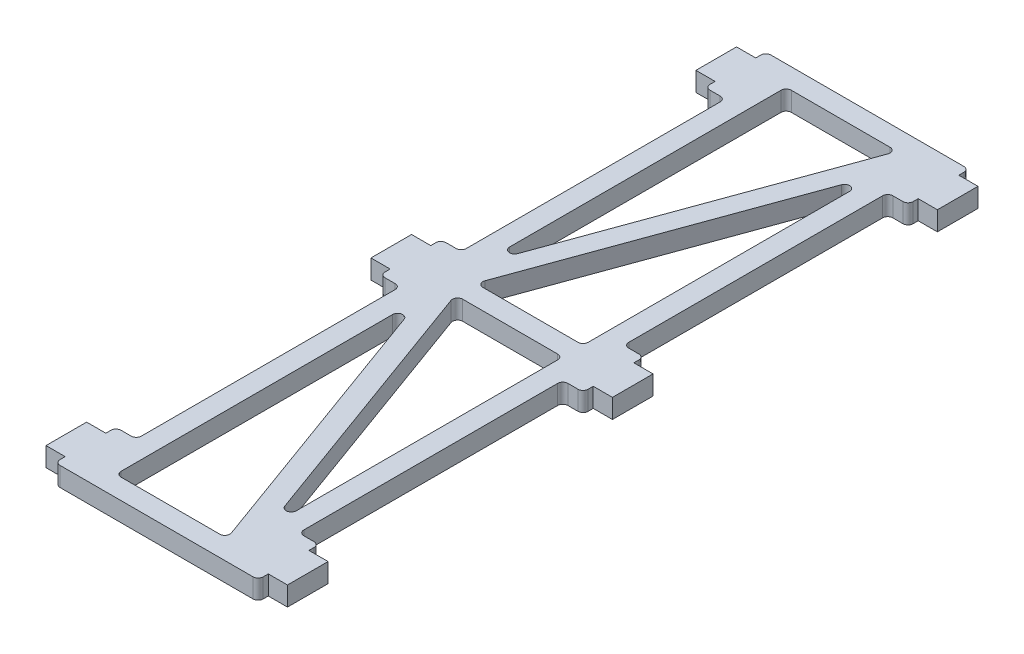
SolidWorks part; units mm, degrees
ref_plane "Front Plane" through (0, 0, 0) normal (0, 0, 1) x (1, 0, 0)
ref_plane "Top Plane" through (0, 0, 0) normal (0, 1, 0) x (1, 0, 0)
ref_plane "Right Plane" through (0, 0, 0) normal (1, 0, 0) x (0, 0, -1)
sketch "Sketch1" plane through (0, 34.29, 0) normal (0, 1, 0) x (1, 0, 0)
  line L0 (16.0528, 190.5) -> (19.05, 190.5) construction
  line L1 (0, -190.5) -> (0, 187.198) construction
  line L2 (38.1028, 187.198) -> (35.1028, 187.198) construction
  line L3 (35.1028, -190.5) -> (38.1, -190.5) construction
  line L5 (-12.7, 65.0875) -> (12.7, 65.0875)
  line L6 (-12.7, 65.0875) -> (-12.7, 176.2125)
  line L7 (-12.7, 176.2125) -> (12.7, 176.2125)
  line L8 (12.7, 65.0875) -> (12.7, 176.2125)
  line L9 (-12.7, 65.0875) -> (12.7, 176.2125) construction
  line L10 (-12.7, 176.2125) -> (12.7, 65.0875) construction
  point P0 (0, 120.65)
  dimension "D1" = 111.125
  dimension "D2" = 25.4
  dimension "D3" = 14.2875
extrude "Boss-Extrude1" add sketch "Sketch1" along normal mid plane 3 contours L7 L8 L5 L6
sketch "Sketch2" plane through (0, 35.79, 0) normal (0, 1, 0) x (1, 0, 0)
  line L0 (0, 176.2125) -> (0, 65.0186) construction
  line L1 (-12.7, 176.2125) -> (12.7, 176.2125) construction
  line L2 (12.7, 120.65) -> (-12.7, 120.65) construction
  line L3 (12.7, 65.0875) -> (12.7, 176.2125) construction
  line L4 (-12.7, 65.0875) -> (-12.7, 176.2125) construction
  line L5 (-15.875, 176.2125) -> (-12.7, 166.6875) construction
  line L6 (15.875, 166.6875) -> (12.7, 166.6875)
  line L7 (15.875, 166.6875) -> (15.875, 176.2125)
  line L8 (15.875, 176.2125) -> (12.7, 176.2125)
  line L9 (12.7, 166.6875) -> (12.7, 176.2125)
  line L10 (15.875, 166.6875) -> (12.7, 176.2125) construction
  line L11 (15.875, 176.2125) -> (12.7, 166.6875) construction
  line L12 (-15.875, 166.6875) -> (-12.7, 176.2125) construction
  line L13 (-12.7, 166.6875) -> (-12.7, 176.2125)
  line L14 (-15.875, 176.2125) -> (-12.7, 176.2125)
  line L15 (-15.875, 166.6875) -> (-15.875, 176.2125)
  line L16 (-15.875, 166.6875) -> (-12.7, 166.6875)
  line L17 (15.875, 115.8875) -> (12.7, 115.8875)
  line L18 (15.875, 115.8875) -> (15.875, 125.4125)
  line L19 (15.875, 125.4125) -> (12.7, 125.4125)
  line L20 (12.7, 115.8875) -> (12.7, 125.4125)
  line L21 (15.875, 115.8875) -> (12.7, 125.4125) construction
  line L22 (15.875, 125.4125) -> (12.7, 115.8875) construction
  line L23 (-12.7, 115.8875) -> (-12.7, 125.4125)
  line L24 (-15.875, 125.4125) -> (-12.7, 125.4125)
  line L25 (-15.875, 115.8875) -> (-15.875, 125.4125)
  line L26 (-15.875, 115.8875) -> (-12.7, 115.8875)
  line L27 (-15.875, 125.4125) -> (-12.7, 115.8875) construction
  line L28 (-15.875, 115.8875) -> (-12.7, 125.4125) construction
  line L29 (15.875, 65.0875) -> (12.7, 65.0875)
  line L30 (15.875, 65.0875) -> (15.875, 74.6125)
  line L31 (15.875, 74.6125) -> (12.7, 74.6125)
  line L32 (12.7, 65.0875) -> (12.7, 74.6125)
  line L33 (15.875, 65.0875) -> (12.7, 74.6125) construction
  line L34 (15.875, 74.6125) -> (12.7, 65.0875) construction
  line L35 (-12.7, 65.0875) -> (-12.7, 74.6125)
  line L36 (-15.875, 74.6125) -> (-12.7, 74.6125)
  line L37 (-15.875, 65.0875) -> (-15.875, 74.6125)
  line L38 (-15.875, 65.0875) -> (-12.7, 65.0875)
  line L39 (-15.875, 74.6125) -> (-12.7, 65.0875) construction
  line L40 (-15.875, 65.0875) -> (-12.7, 74.6125) construction
  point P11 (14.2875, 171.45)
  point P21 (-14.2875, 171.45)
  point P24 (14.2875, 120.65)
  point P33 (-14.2875, 120.65)
  point P34 (14.2875, 69.85)
  point P43 (-14.2875, 69.85)
  dimension "D1" = 3.175
  dimension "D2" = 9.525
  dimension "D3" = 3
extrude "Boss-Extrude2" add sketch "Sketch2" against normal up to surface (3 mm away) up to face at (0, 32.79, -120.65)
sketch "Sketch4" plane through (0, 35.79, 0) normal (0, 1, 0) x (1, 0, 0)
  line L0 (12.7, 125.4125) -> (12.7, 166.6875) construction
  line L1 (-9.525, 173.0375) -> (9.525, 173.0375)
  line L2 (-9.525, 173.0375) -> (-9.525, 68.2625)
  line L3 (-9.525, 68.2625) -> (9.525, 68.2625)
  line L4 (9.525, 173.0375) -> (9.525, 68.2625)
  line L5 (-9.525, 173.0375) -> (9.525, 68.2625) construction
  line L6 (-9.525, 68.2625) -> (9.525, 173.0375) construction
  line L7 (-12.7, 125.4125) -> (-12.7, 166.6875) construction
  line L8 (-15.875, 176.2125) -> (15.875, 176.2125) construction
  line L9 (-15.875, 65.0875) -> (15.875, 65.0875) construction
  line L10 (-9.525, 120.65) -> (9.525, 120.65) construction
  line L11 (9.525, 120.65) -> (-9.525, 173.0375) construction
  line L12 (9.525, 120.65) -> (-9.525, 68.2625) construction
  line L13 (-9.525, 120.65) -> (9.525, 173.0375) construction
  line L14 (9.525, 68.2625) -> (-9.525, 120.65) construction
  line L15 (-9.525, 119.0625) -> (9.525, 119.0625)
  line L16 (-9.525, 122.2375) -> (9.525, 122.2375)
  line L17 (11.0169, 68.805) -> (-7.8358, 120.65)
  line L18 (-7.8358, 120.65) -> (11.0169, 172.495)
  line L19 (11.2142, 120.65) -> (-8.0331, 67.72) construction
  line L20 (11.2142, 120.65) -> (-8.0331, 173.58) construction
  line L21 (8.0331, 67.72) -> (-11.2142, 120.65)
  line L22 (-11.2142, 120.65) -> (8.0331, 173.58)
  line L23 (7.8358, 120.65) -> (-11.0169, 68.805) construction
  line L24 (7.8358, 120.65) -> (-11.0169, 172.495) construction
  point P0 (0, 120.65)
  dimension "D1" = 3.175
  dimension "D2" = 3.175
  dimension "D3" = 3.175
  dimension "D4" = 3.175
  dimension "D5" = 1.5875
  dimension "D6" = 1.5875
  dimension "D7" = 1.5875
  dimension "D8" = 1.5875
extrude "Cut-Extrude1" cut sketch "Sketch4" against normal blind 3 contours L2 L22 L1 | L18 L16 L4 | L17 L4 L15 | L3 L21 L2
fillet "Fillet1" radius 0.7937 32 edges at (-7.2585, 34.29, -119.0625) (-9.525, 34.29, -116.0047) (9.525, 34.29, -168.3922) (7.8358, 34.29, -173.0375) (9.525, 34.29, -72.9078) (15.875, 34.29, -65.0875) (15.875, 34.29, -74.6125) (12.7, 34.29, -74.6125) (12.7, 34.29, -115.8875) (15.875, 34.29, -115.8875) (15.875, 34.29, -125.4125) (12.7, 34.29, -125.4125) (12.7, 34.29, -166.6875) (15.875, 34.29, -166.6875) (15.875, 34.29, -176.2125) (-15.875, 34.29, -166.6875) (-12.7, 34.29, -166.6875) (-12.7, 34.29, -125.4125) (-15.875, 34.29, -125.4125) (-15.875, 34.29, -115.8875) (-12.7, 34.29, -115.8875) (-12.7, 34.29, -74.6125) (-15.875, 34.29, -74.6125) (-15.875, 34.29, -65.0875) (-9.525, 34.29, -125.2953) (7.8358, 34.29, -68.2625) (-7.2585, 34.29, -122.2375) (-15.875, 34.29, -176.2125) (9.525, 34.29, -122.2375) (9.525, 34.29, -119.0625) (-9.525, 34.29, -68.2625) (-9.525, 34.29, -173.0375)
sketch "Sketch5" plane through (0, 35.79, 0) normal (0, 1, 0) x (1, 0, 0)
  line L0 (15.875, 167.4813) -> (15.875, 175.4188) construction
  line L1 (18.875, 168.275) -> (15.875, 168.275)
  line L2 (18.875, 168.275) -> (18.875, 174.625)
  line L3 (18.875, 174.625) -> (15.875, 174.625)
  line L4 (15.875, 168.275) -> (15.875, 174.625)
  line L5 (18.875, 168.275) -> (15.875, 174.625) construction
  line L6 (18.875, 174.625) -> (15.875, 168.275) construction
  line L7 (15.875, 167.4813) -> (15.875, 175.4188) construction
  line L8 (15.875, 171.45) -> (17.375, 171.45) construction
  line L9 (0, 196.0278) -> (0, 0) construction
  line L10 (-15.875, 171.45) -> (-17.375, 171.45) construction
  line L11 (-18.875, 174.625) -> (-15.875, 168.275) construction
  line L12 (-18.875, 168.275) -> (-15.875, 174.625) construction
  line L13 (-15.875, 168.275) -> (-15.875, 174.625)
  line L14 (-18.875, 174.625) -> (-15.875, 174.625)
  line L15 (-18.875, 168.275) -> (-18.875, 174.625)
  line L16 (-18.875, 168.275) -> (-15.875, 168.275)
  line L17 (18.875, 117.475) -> (15.875, 117.475)
  line L18 (18.875, 117.475) -> (18.875, 123.825)
  line L19 (18.875, 123.825) -> (15.875, 123.825)
  line L20 (15.875, 117.475) -> (15.875, 123.825)
  line L21 (18.875, 117.475) -> (15.875, 123.825) construction
  line L22 (18.875, 123.825) -> (15.875, 117.475) construction
  line L23 (15.875, 120.65) -> (17.375, 120.65) construction
  line L24 (-15.875, 117.475) -> (-15.875, 123.825)
  line L25 (-18.875, 123.825) -> (-15.875, 123.825)
  line L26 (-18.875, 117.475) -> (-18.875, 123.825)
  line L27 (-18.875, 117.475) -> (-15.875, 117.475)
  line L28 (-15.875, 120.65) -> (-17.375, 120.65) construction
  line L29 (-18.875, 123.825) -> (-15.875, 117.475) construction
  line L30 (-18.875, 117.475) -> (-15.875, 123.825) construction
  line L31 (18.875, 66.675) -> (15.875, 66.675)
  line L32 (18.875, 66.675) -> (18.875, 73.025)
  line L33 (18.875, 73.025) -> (15.875, 73.025)
  line L34 (15.875, 66.675) -> (15.875, 73.025)
  line L35 (18.875, 66.675) -> (15.875, 73.025) construction
  line L36 (18.875, 73.025) -> (15.875, 66.675) construction
  line L37 (15.875, 69.85) -> (17.375, 69.85) construction
  line L38 (-15.875, 66.675) -> (-15.875, 73.025)
  line L39 (-18.875, 73.025) -> (-15.875, 73.025)
  line L40 (-18.875, 66.675) -> (-18.875, 73.025)
  line L41 (-18.875, 66.675) -> (-15.875, 66.675)
  line L42 (-15.875, 69.85) -> (-17.375, 69.85) construction
  line L43 (-18.875, 73.025) -> (-15.875, 66.675) construction
  line L44 (-18.875, 66.675) -> (-15.875, 73.025) construction
  line L45 (-17.375, 171.45) -> (-17.375, 120.65) construction
  point P0 (17.375, 171.45)
  point P7 (17.375, 120.65)
  point P21 (-17.375, 171.45)
  point P35 (-17.375, 120.65)
  point P36 (17.375, 69.85)
  point P49 (-17.375, 69.85)
  dimension "D1" = 3
  dimension "D2" = 6.35
  dimension "D4" = 50.8
  dimension "D3" = 3
extrude "Boss-Extrude3" add sketch "Sketch5" against normal up to surface (3 mm away)
